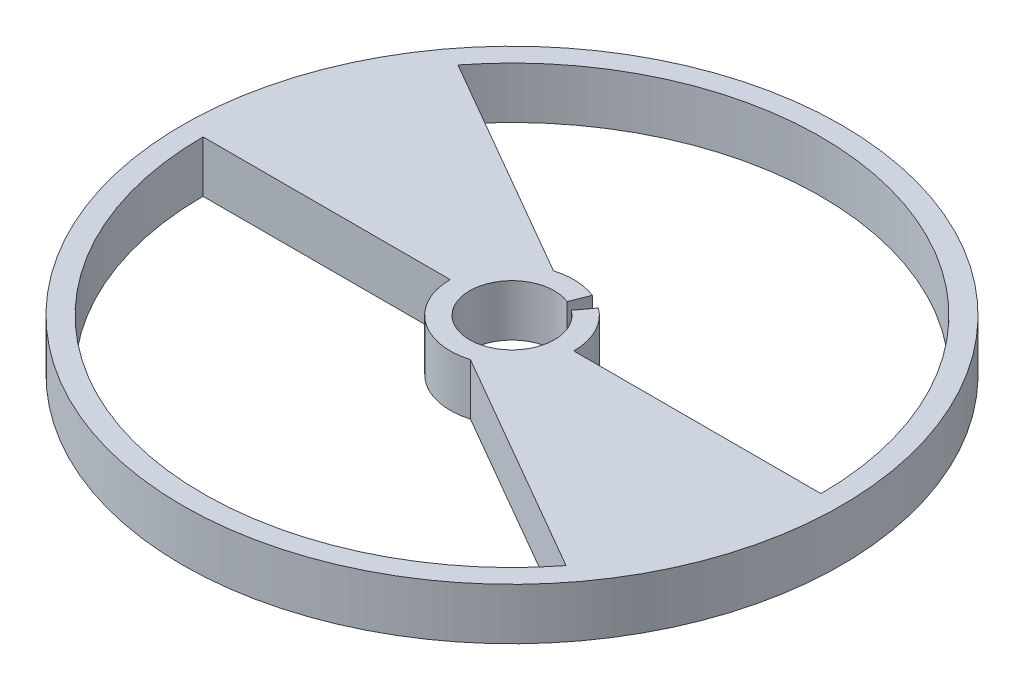
SolidWorks part; units mm, degrees
ref_plane "Front Plane" through (0, 0, 0) normal (0, 0, 1) x (1, 0, 0)
ref_plane "Top Plane" through (0, 0, 0) normal (0, 1, 0) x (1, 0, 0)
ref_plane "Right Plane" through (0, 0, 0) normal (1, 0, 0) x (0, 0, -1)
sketch "Sketch1" plane through (0, 0, 0) normal (0, 1, 0) x (1, 0, 0)
  line L0 (-3, 0) -> (-15, 0)
  line L1 (-11.8373, 9.2129) -> (-0.8587, 2.8745)
  line L2 (3, 0) -> (15, 0)
  line L3 (0.8587, -2.8745) -> (11.8373, -9.2129)
  circle A0 centre (0, 0) radius 16
  arc A1 (-15, 0) -> (11.8373, -9.2129) centre (0, 0) ccw
  circle A2 centre (0, 0) radius 2.06
  arc A3 (3, 0) -> (-0.8587, 2.8745) centre (0, 0) ccw
  arc A4 (15, 0) -> (-11.8373, 9.2129) centre (0, 0) ccw
  arc A5 (-3, 0) -> (0.8587, -2.8745) centre (0, 0) ccw
  dimension "D2" = 30
  dimension "D3" = 4.12
  dimension "D4" = 6
  dimension "D5" = 30
  dimension "D6" = 30
  dimension "D1" = 1
extrude "Boss-Extrude1" add sketch "Sketch1" along normal blind 2.5
sketch "Sketch2" plane through (0, 2.5, 0) normal (0, 1, 0) x (1, 0, 0)
  line L0 (0, 0) -> (1.1084, 2.7877)
  line L1 (1.1084, 2.7877) -> (0, 0)
  line L2 (0, 0) -> (1.7922, 2.4058)
  arc A0 (3, 0) -> (-0.8587, 2.8745) centre (0, 0) ccw construction
  arc A1 (1.1084, 2.7877) -> (1.7922, 2.4058) centre (0, 0) ccw
  circle M4 centre (0, 0) radius 2.06
  arc M12 (3, 0) -> (-0.8587, 2.8745) centre (0, 0) ccw
  dimension "D1" = 15
extrude "Cut-Extrude1" cut sketch "Sketch2" against normal through all contours L2 L0 M4 M12
equation "\"D6@Sketch1\"=\"D5@Sketch1\""
